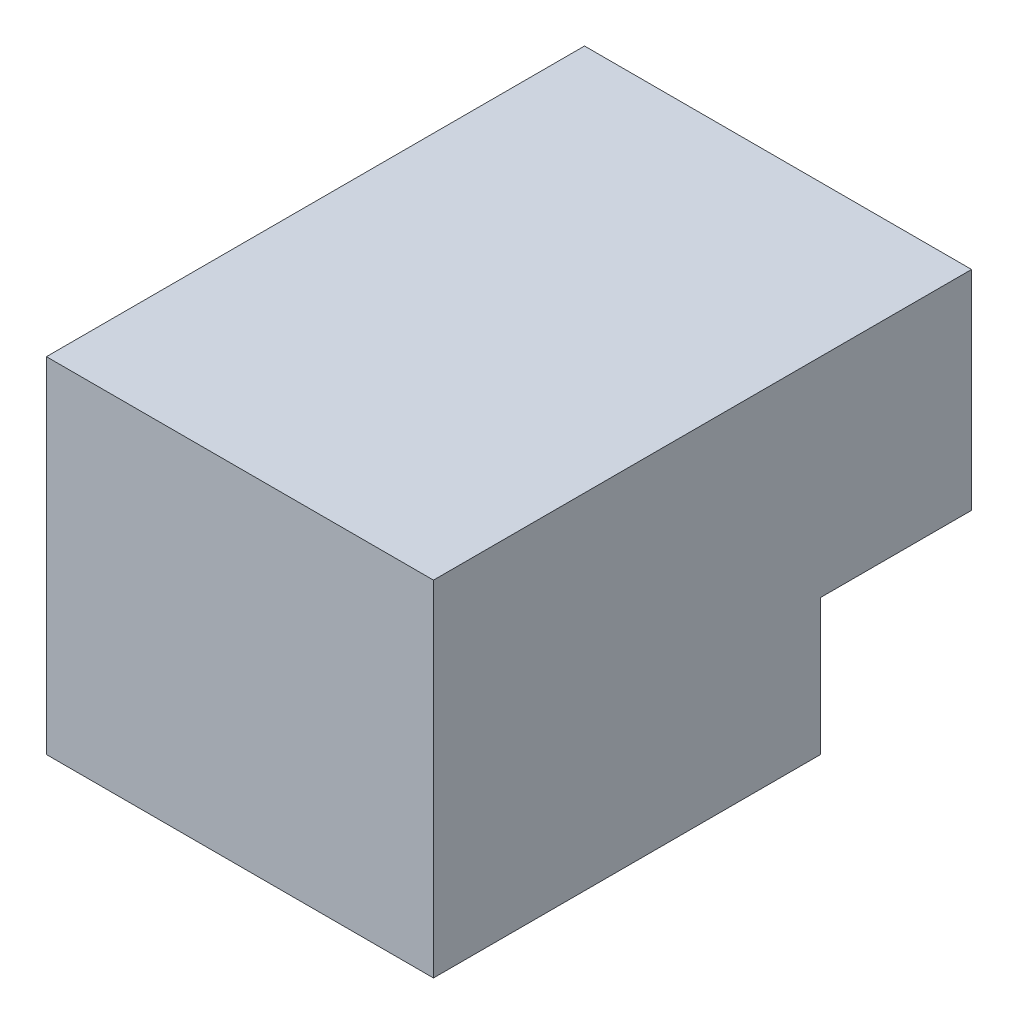
SolidWorks part; units mm, degrees
material "ABS"
ref_plane "X-Y Datum" through (0, 0, 0) normal (0, 0, 1) x (1, 0, 0)
ref_plane "X-Z Datum" through (0, 0, 0) normal (0, 1, 0) x (1, 0, 0)
ref_plane "Y-Z Datum" through (0, 0, 0) normal (1, 0, 0) x (0, 0, -1)
sketch "Sketch1" plane through (0, 0, 0) normal (0, 1, 0) x (1, 0, 0)
  line L0 (-2.54, -2.54) -> (-2.54, 62.54)
  line L1 (0, 0) -> (60, 0)
  line L2 (0, 0) -> (0, 60)
  line L3 (0, 60) -> (60, 60)
  line L4 (60, 0) -> (60, 60)
  line L5 (-2.54, 62.54) -> (62.54, 62.54)
  line L6 (62.54, -2.54) -> (62.54, 62.54)
  line L7 (-2.54, -2.54) -> (62.54, -2.54)
  dimension "D1" = 2.54
extrude "Boss-Extrude1" add sketch "Sketch1" along normal blind 25.4
sketch "Sketch2" plane through (0, 0, -62.54) normal (0, 0, -1) x (-1, 0, 0)
  line L5 (-62.54, 25.4) -> (2.54, 25.4) construction
  line L7 (0, 25.4) -> (0, 55.4)
  line L8 (0, 55.4) -> (-60, 55.4)
  line L9 (-60, 55.4) -> (-60, 25.4)
  line L10 (-60, 55.4) -> (-60, 57.94) construction
  line L11 (-62.54, 25.4) -> (-62.54, 57.94)
  line L12 (-62.54, 57.94) -> (2.54, 57.94)
  line L13 (2.54, 57.94) -> (2.54, 25.4)
  line L21 (-62.54, 25.4) -> (-60, 25.4)
  line L22 (0, 25.4) -> (2.54, 25.4)
extrude "Boss-Extrude2" add sketch "Sketch2" along normal blind 25.4 and the other way up to surface (65.08 mm away) other way up to face at (30, 12.7, 2.54)
sketch "Sketch4" plane through (0, 0, -62.54) normal (0, 0, -1) x (-1, 0, 0)
  line L0 (2.54, 25.4) -> (2.54, 0) construction
  line L1 (-62.54, 25.4) -> (2.54, 25.4)
  line L2 (-62.54, 25.4) -> (-62.54, 22.86)
  line L3 (-62.54, 22.86) -> (2.54, 22.86)
  line L4 (2.54, 25.4) -> (2.54, 22.86)
extrude "Boss-Extrude3" add sketch "Sketch4" along normal blind 25.4
sketch "Sketch5" plane through (0, 0, 2.54) normal (0, 0, 1) x (1, 0, 0)
  line L1 (0, 25.4) -> (60, 25.4)
  line L2 (0, 25.4) -> (0, 55.4)
  line L3 (0, 55.4) -> (60, 55.4)
  line L4 (60, 25.4) -> (60, 55.4)
extrude "Boss-Extrude4" add sketch "Sketch5" against normal up to surface (2.54 mm away) up to face at (30, 12.7, 0)
